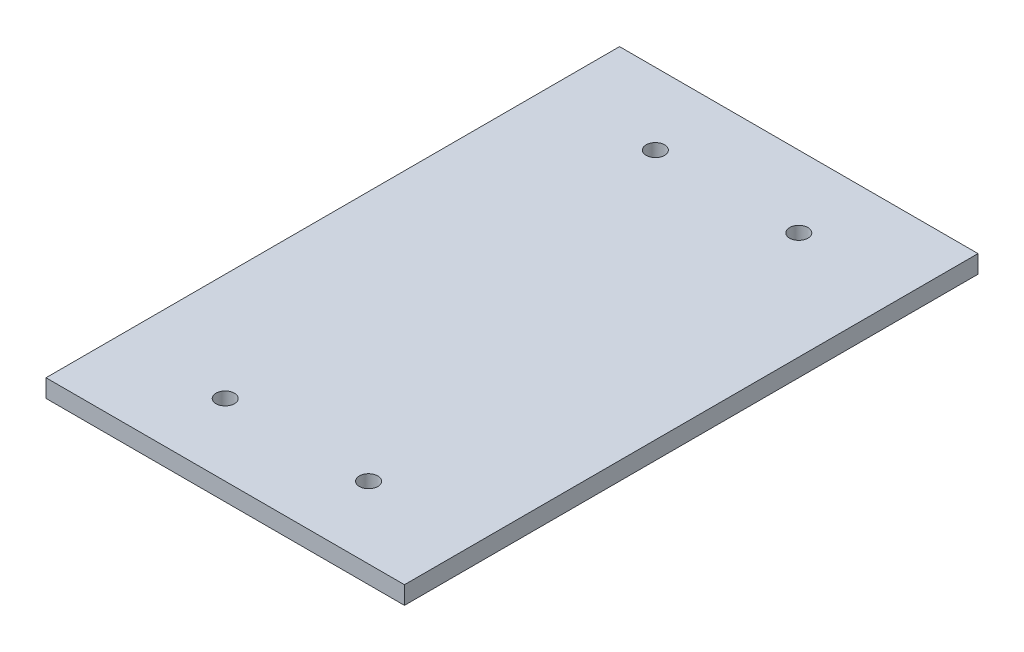
SolidWorks part; units mm, degrees
ref_plane "Front Plane" through (0, 0, 0) normal (0, 0, 1) x (1, 0, 0)
ref_plane "Top Plane" through (0, 0, 0) normal (0, 1, 0) x (1, 0, 0)
ref_plane "Right Plane" through (0, 0, 0) normal (1, 0, 0) x (0, 0, -1)
sketch "Sketch1" plane through (0, 0, 0) normal (0, 1, 0) x (1, 0, 0)
  line L1 (-63.5, 101.6) -> (63.5, 101.6)
  line L2 (-63.5, 101.6) -> (-63.5, -101.6)
  line L3 (-63.5, -101.6) -> (63.5, -101.6)
  line L4 (63.5, 101.6) -> (63.5, -101.6)
  line L5 (-63.5, 101.6) -> (63.5, -101.6) construction
  line L6 (-63.5, -101.6) -> (63.5, 101.6) construction
  point P0 (0, 0)
  dimension "D1" = 203.2
  dimension "D2" = 127
extrude "Boss-Extrude1" add sketch "Sketch1" along normal blind 6.35
hole_wizard "5/16-18 Tapped Hole1" positions "Sketch3" profile "Sketch4" tap size "5/16-18" standard "ANSI Inch" end condition through all
sketch "Sketch3" plane through (0, 6.35, 0) normal (0, 1, 0) x (1, 0, 0)
  line L0 (63.5, 101.6) -> (-63.5, 101.6) construction
  line L1 (-63.5, 101.6) -> (-63.5, -101.6) construction
  line L3 (-63.5, -101.6) -> (63.5, -101.6) construction
  point P0 (-25.4, 76.2)
  point P2 (25.4, 76.2)
  point P4 (25.4, -76.2)
  point P6 (-25.4, -76.2)
  dimension "D1" = 25.4
  dimension "D2" = 38.1
  dimension "D3" = 88.9
  dimension "D4" = 88.9
  dimension "D5" = 38.1
  dimension "D6" = 25.4
  dimension "D7" = 25.4
  dimension "D8" = 25.4
sketch "Sketch4" plane through (-25.4, 6.35, -76.2) normal (1, 0, 0) x (0, 0, 1)
  line L0 (0, 0) -> (0, 6.35)
  line L1 (0, 6.35) -> (3.2639, 6.35)
  line L2 (3.2639, 6.35) -> (3.2639, 0)
  line L5 (3.2639, 0) -> (0, 0)
  line L11 (0, -6.35) -> (0, 107.95) construction
  dimension "Thru Tap Drill Dia." = 6.5278
  dimension "Thru Tap Drill Depth" = 6.35
cosmetic thread "Hole Thread1" parameters "D2"=7.9375
cosmetic thread "Hole Thread2" parameters "D2"=7.9375
cosmetic thread "Hole Thread3" parameters "D2"=7.9375
cosmetic thread "Hole Thread4" parameters "D2"=7.9375
